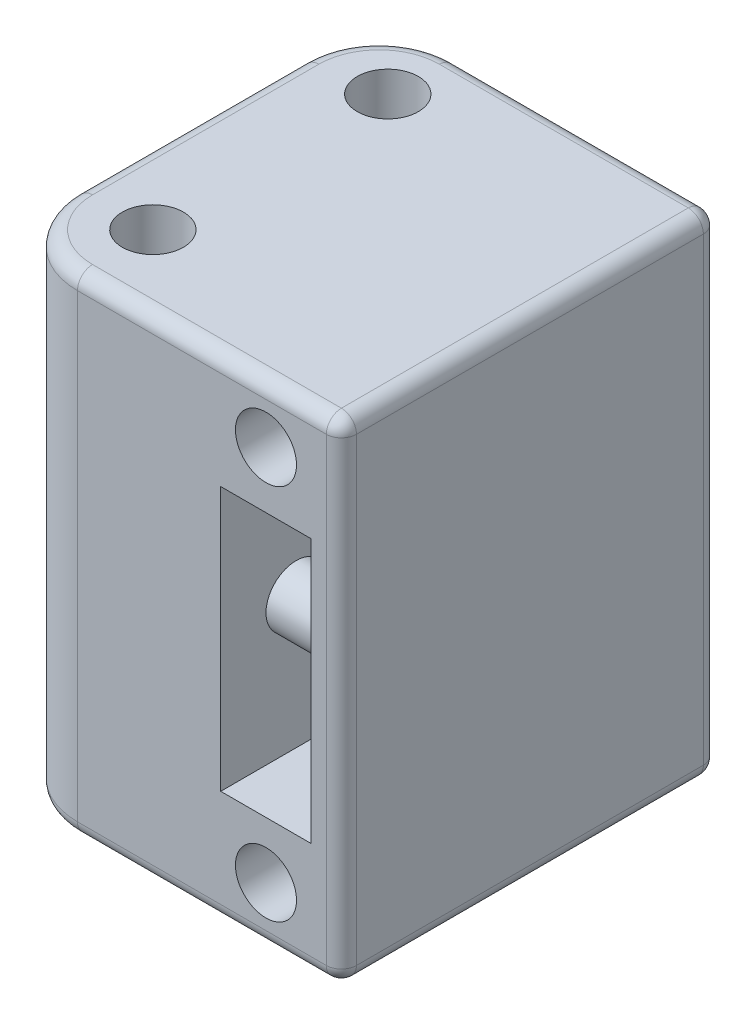
SolidWorks part; units mm, degrees
ref_plane "Front (XY)" through (0, 0, 0) normal (0, 0, 1) x (1, 0, 0)
ref_plane "Top (XZ)" through (0, 0, 0) normal (0, 1, 0) x (1, 0, 0)
ref_plane "Right (YZ)" through (0, 0, 0) normal (1, 0, 0) x (0, 0, -1)
sketch "Sketch1" plane through (0, 0, 0) normal (0, 1, 0) x (1, 0, 0)
  circle A0 centre (0, 0) radius 10
  dimension "D1" = 20
extrude "Boss-Extrude1" add sketch "Sketch1" against normal blind 65
sketch "Sketch2" plane through (0, 0, 0) normal (0, 1, 0) x (1, 0, 0)
  line L0 (0, -10) -> (35, -10)
  line L1 (-10, 0) -> (-10, 40)
  line L2 (-10, 40) -> (35, 40)
  line L3 (35, 40) -> (35, -10)
  circle A0 centre (0, 0) radius 10 construction
  arc A1 (-10, 0) -> (0, -10) centre (0, 0) ccw
  dimension "D1" = 35
  dimension "D2" = 40
  dimension "D3" = 50
  dimension "D4" = 45
extrude "Boss-Extrude2" add sketch "Sketch2" against normal blind 10
sketch "Sketch3" plane through (0, 0, 0) normal (0, 1, 0) x (1, 0, 0)
  line L0 (35, -10) -> (35, 40) construction
  line L1 (0, -10) -> (35, -10) construction
  line L2 (35, -10) -> (35, 40)
  line L3 (0, -10) -> (35, -10)
  line L4 (35, 40) -> (-10, 40) construction
  line L5 (35, 40) -> (15, 40)
  line L6 (15, 40) -> (15, 10)
  line L7 (0, 10) -> (15, 10)
  arc A0 (0, -10) -> (-10, 0) centre (0, 0) ccw construction
  arc A1 (0, 10) -> (-10, 0) centre (0, 0) ccw
  arc A2 (-10, 0) -> (0, -10) centre (0, 0) ccw construction
  arc A3 (-10, 0) -> (0, -10) centre (0, 0) ccw
  dimension "D1" = 20
extrude "Boss-Extrude3" add sketch "Sketch3" against normal up to surface (65 mm away) up to face at (0, -65, 10)
sketch "Sketch4" plane through (0, 0, 0) normal (0, 1, 0) x (1, 0, 0)
  line L1 (35, 40) -> (-10, 40) construction
  circle A0 centre (0, 0) radius 4.05
  circle A1 centre (0, 31.15) radius 4.05
  dimension "D1" = 8.1
  dimension "D2" = 8.1
  dimension "D3" = 31.15
  dimension "D4" = 8.85
extrude "Cut-Extrude1" cut sketch "Sketch4" against normal through all
fillet "Fillet1" radius 10 1 edges at (-10, -5, -40)
fillet "Fillet2" radius 2 14 edges at (7.5, -65, -10) (-10, -65, 0) (17.5, 0, -40) (-7.0711, 0, -37.0711) (-10, 0, -15) (-7.0711, 0, 7.0711) (35, -32.5, -40) (35, 0, -15) (35, -65, -15) (25, -65, -40) (15, -65, -25) (17.5, 0, 10) (17.5, -65, 10) (35, -32.5, 10)
sketch "Sketch6" plane through (0, 0, -40) normal (0, 0, -1) x (-1, 0, 0)
  line L0 (-33, 0) -> (0, 0) construction
  circle A0 centre (-24.9991, -7.5) radius 4.05
  circle A1 centre (-24.9991, -57.5) radius 4.05
  dimension "D4" = 8.1
  dimension "D1" = 50
  dimension "D2" = 7.5
  dimension "D3" = 24.9991
extrude "Cut-Extrude2" cut sketch "Sketch6" against normal through all both and the other way through all
sketch "Sketch7" plane through (0, 0, -40) normal (0, 0, -1) x (-1, 0, 0)
  line L0 (-31, -15) -> (-31, -50)
  line L1 (-31, -50) -> (-19, -50)
  line L2 (-19, -50) -> (-19, -15)
  line L3 (-19, -15) -> (-31, -15)
  line L4 (-33, 0) -> (0, 0) construction
  point P4 (-25, -15)
  dimension "D1" = 35
  dimension "D2" = 12
  dimension "D3" = 25
  dimension "D4" = 15
extrude "Cut-Extrude3" cut sketch "Sketch7" against normal through all
sketch "Sketch8" plane through (31, 0, 0) normal (-1, 0, 0) x (0, 0, 1)
  line L0 (0, 0) -> (0, -32.5) construction
  circle A0 centre (0, -32.5) radius 4
  dimension "D1" = 8
  dimension "D2" = 32.5
extrude "Boss-Extrude4" add sketch "Sketch8" along normal up to next
